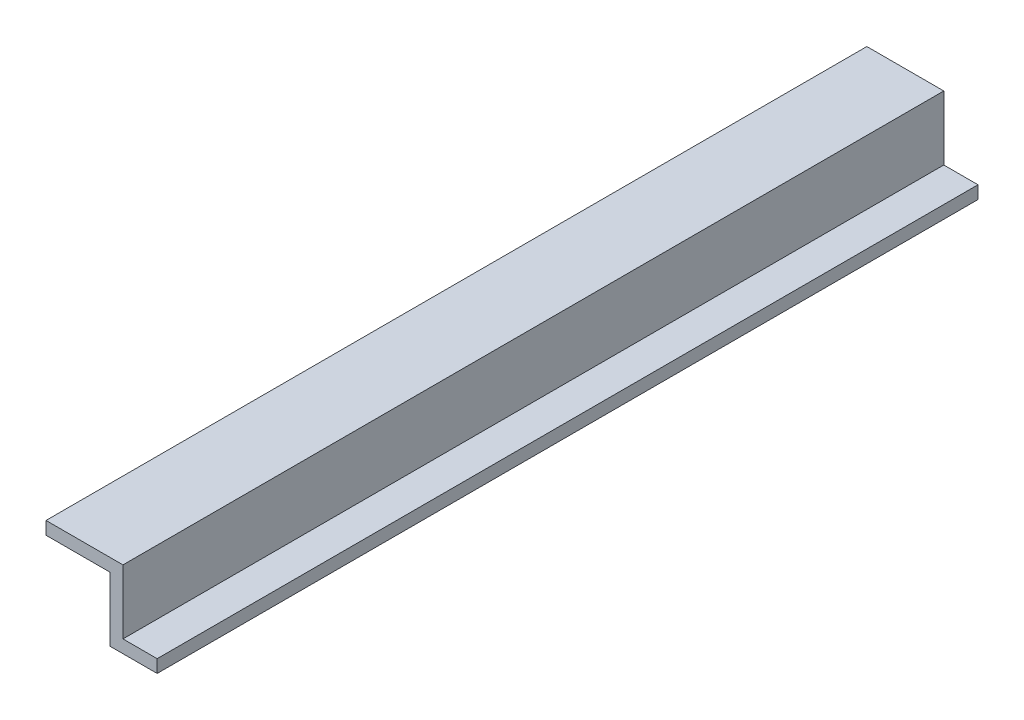
SolidWorks part; units mm, degrees
ref_plane "Front Plane" through (0, 0, 0) normal (0, 0, 1) x (1, 0, 0)
ref_plane "Top Plane" through (0, 0, 0) normal (0, 1, 0) x (1, 0, 0)
ref_plane "Right Plane" through (0, 0, 0) normal (1, 0, 0) x (0, 0, -1)
sketch "Sketch1" plane through (0, 0, 0) normal (0, 0, 1) x (1, 0, 0)
  line L0 (0, -11.9062) -> (0, 11.9062) construction
  line L1 (0, 11.9062) -> (-26.1938, 11.9062) construction
  line L2 (0, -11.9062) -> (26.1938, -11.9062) construction
  line L3 (2.3812, -9.525) -> (26.1938, -9.525) construction
  line L4 (2.3812, -9.525) -> (2.3812, 14.2875) construction
  line L5 (2.3812, 14.2875) -> (-26.1938, 14.2875) construction
  line L6 (-2.3812, -14.2875) -> (26.1938, -14.2875) construction
  line L7 (-2.3812, -14.2875) -> (-2.3812, 9.525) construction
  line L8 (-2.3812, 9.525) -> (-26.1938, 9.525) construction
  line L9 (-26.1938, 14.2875) -> (-26.1938, 9.525) construction
  line L10 (26.1938, -9.525) -> (26.1938, -14.2875) construction
  point P4 (0, 0)
  dimension "Leg Width" = 28.575
  dimension "Outside Height" = 28.575
  dimension "Wall Thickness" = 4.7625
sketch "Sketch2" plane through (0, 0, 0) normal (1, 0, 0) x (0, 0, -1)
  line L0 (152.4, 0) -> (-152.4, 0) construction
  line L1 (0, 0) -> (0, 14.2875) construction
  line L2 (-152.4, 0) -> (-152.4, 14.2875) construction
  line L3 (152.4, 0) -> (152.4, 14.2875) construction
  point P0 (-114.3, 0)
  point P3 (114.3, 0)
  point P4 (0, 0)
  dimension "D1" = 228.6
  dimension "Length" = 304.8
sketch "Sketch3" plane through (0, 0, 0) normal (0, 0, 1) x (1, 0, 0)
  line L1 (2.3812, -9.525) -> (26.1938, -9.525) construction
  line L2 (-2.3812, -14.2875) -> (26.1938, -14.2875) construction
  line L3 (-2.3812, -14.2875) -> (-2.3812, 9.525) construction
  line L4 (2.3812, -9.525) -> (2.3812, 14.2875) construction
  line L5 (2.3812, 14.2875) -> (-26.1938, 14.2875) construction
  line L6 (-26.1938, 14.2875) -> (-26.1938, 9.525) construction
  line L7 (-2.3812, 9.525) -> (-26.1938, 9.525) construction
  line L8 (15.0812, -9.525) -> (15.0812, -14.2875)
  line L9 (2.3812, -9.525) -> (15.0812, -9.525)
  line L10 (-2.3812, -14.2875) -> (15.0812, -14.2875)
  line L11 (-2.3812, -14.2875) -> (-2.3812, 9.525)
  line L12 (2.3812, -9.525) -> (2.3812, 14.2875)
  line L13 (2.3812, 14.2875) -> (-26.1938, 14.2875)
  line L14 (-26.1938, 14.2875) -> (-26.1938, 9.525)
  line L15 (-2.3812, 9.525) -> (-26.1938, 9.525)
extrude "Boss-Extrude1" add sketch "Sketch3" along normal up to vertex (152.4 mm away) and the other way up to vertex (152.4 mm away) up to point (0, 0, 152.4) other way up to point (0, 0, -152.4)
equation "\"D1@Sketch2\"=\"Length@Sketch2\"*0.75"
